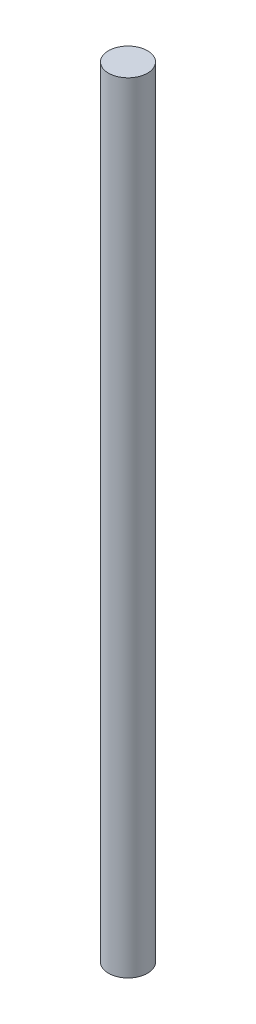
SolidWorks part; units mm, degrees
material "Stainless Steel (ferritic)"
ref_plane "Front Plane" through (0, 0, 0) normal (0, 0, 1) x (1, 0, 0)
ref_plane "Top Plane" through (0, 0, 0) normal (0, 1, 0) x (1, 0, 0)
ref_plane "Right Plane" through (0, 0, 0) normal (1, 0, 0) x (0, 0, -1)
sketch "Sketch1" plane through (0, 0, 0) normal (0, 1, 0) x (1, 0, 0)
  circle A0 centre (0, 0) radius 2.5
  dimension "D1" = 5
extrude "Boss-Extrude1" add sketch "Sketch1" along normal mid plane 100
